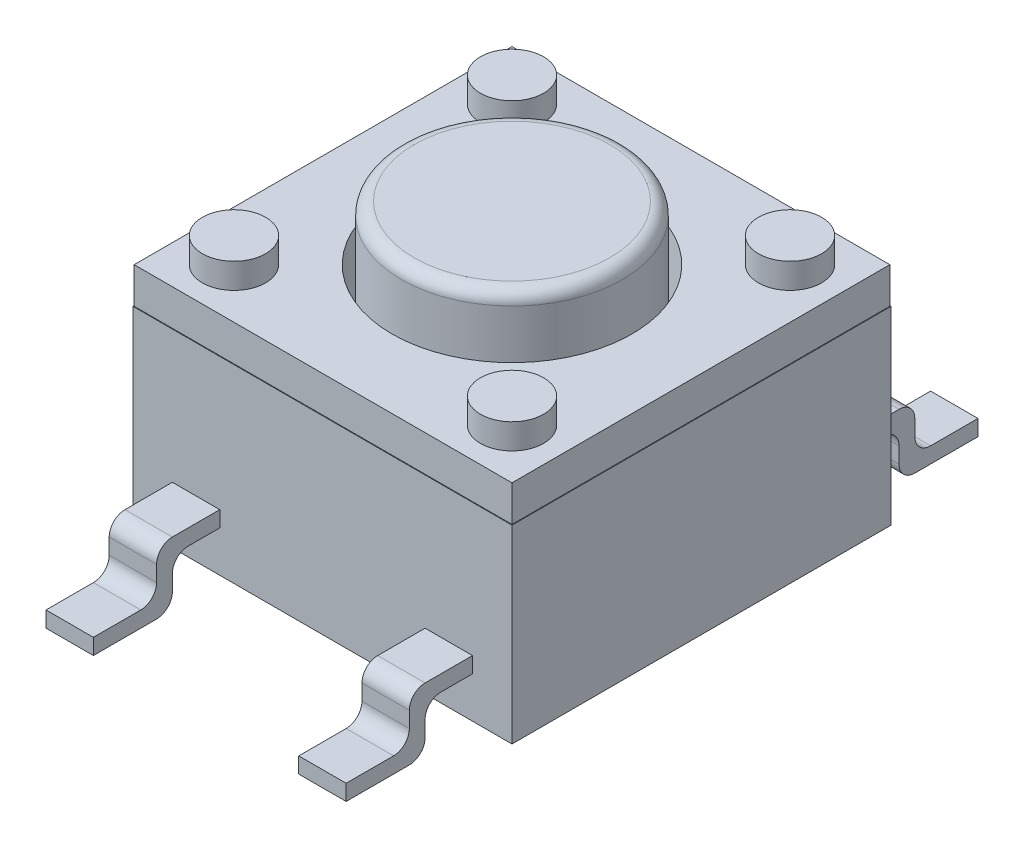
SolidWorks part; units mm, degrees
ref_plane "Front Plane" through (0, 0, 0) normal (0, 0, 1) x (1, 0, 0)
ref_plane "Top Plane" through (0, 0, 0) normal (0, 1, 0) x (1, 0, 0)
ref_plane "Right Plane" through (0, 0, 0) normal (1, 0, 0) x (0, 0, -1)
sketch "Sketch1" plane through (0, 0, 0) normal (0, 1, 0) x (1, 0, 0)
  line L1 (-3, 3) -> (3, 3)
  line L2 (-3, 3) -> (-3, -3)
  line L3 (-3, -3) -> (3, -3)
  line L4 (3, 3) -> (3, -3)
  circle A0 centre (0, 0) radius 1.9
  point P4 (-3, 0)
  point P6 (0, 3)
  dimension "D2" = 3.8
  dimension "D1" = 6
extrude "Extrude1" add sketch "Sketch1" along normal blind 3
sketch "Sketch2" plane through (0, 3, 0) normal (0, 1, 0) x (1, 0, 0)
  line L8 (-2.99, 2.99) -> (-2.99, -2.99)
  line L9 (-2.99, -2.99) -> (2.99, -2.99)
  line L10 (2.99, -2.99) -> (2.99, 2.99)
  line L11 (2.99, 2.99) -> (-2.99, 2.99)
  line L12 (-2.99, 2.99) -> (-2.99, -2.99)
  line L13 (-2.99, -2.99) -> (2.99, -2.99)
  line L14 (2.99, -2.99) -> (2.99, 2.99)
  line L15 (2.99, 2.99) -> (-2.99, 2.99)
  circle A0 centre (0, 0) radius 1.9 construction
  circle A1 centre (0, 0) radius 1.9
  dimension "D1" = 0.01
extrude "Extrude2" add sketch "Sketch2" along normal blind 0.57
sketch "Sketch3" plane through (0, 3.57, 0) normal (0, 1, 0) x (1, 0, 0)
  line L0 (-3, 3) -> (-3, -3) construction
  line L1 (3, 3) -> (-3, 3) construction
  line L2 (3, -3) -> (3, 3) construction
  line L3 (-3, -3) -> (3, -3) construction
  circle A0 centre (-2.2, 2.2) radius 0.5
  circle A1 centre (2.2, 2.2) radius 0.5
  circle A2 centre (2.2, -2.2) radius 0.5
  circle A3 centre (-2.2, -2.2) radius 0.5
  dimension "D1" = 1
  dimension "D2" = 0.8
  dimension "D3" = 0.8
  dimension "D4" = 0.8
  dimension "D5" = 0.8
extrude "Extrude3" add sketch "Sketch3" along normal blind 0.4
sketch "Sketch4" plane through (0, 3.57, 0) normal (0, 1, 0) x (1, 0, 0)
  circle A0 centre (0, 0) radius 1.75
  dimension "D1" = 3.5
extrude "Extrude4" add sketch "Sketch4" along normal blind 0.87 and the other way blind 3
fillet "Fillet1" radius 0.2 1 edges at (0, 4.44, 1.75)
ref_plane "Plane1" through (2, 0, 0) normal (1, 0, 0) x (0, 0, -1)
sketch "Sketch5" plane through (2, 0, 0) normal (1, 0, 0) x (0, 0, -1)
  line L0 (3.75, 0.9) -> (3.75, 0.15) construction
  line L1 (-5, 0.15) -> (-4, 0.15)
  line L2 (-5, -0.1) -> (-3.75, -0.1)
  line L3 (0, 5.8909) -> (0, -2.7526) construction
  line L4 (-5, 0.15) -> (-5, -0.1)
  line L5 (5, 0.15) -> (5, -0.1)
  line L6 (-4, 0.9) -> (-3, 0.9)
  line L7 (-3, 0) -> (3, 0) construction
  line L8 (-3, 0.9) -> (3, 0.9) construction
  line L9 (-3, -0.1) -> (3, -0.1) construction
  line L10 (4, 0.9) -> (4, 0.15) construction
  line L11 (-4, 0.9) -> (-4, 0.15) construction
  line L12 (-4, 3) -> (-4, 0)
  line L13 (-4, 0.9) -> (-4, 0.15)
  line L14 (5, 5.8909) -> (5, -2.7526) construction
  line L15 (4, 3) -> (4, 0)
  line L16 (4, 0.9) -> (4, 0.15)
  line L17 (-5, 5.8909) -> (-5, -2.7526) construction
  line L18 (-3.75, 0.65) -> (-3, 0.65)
  line L19 (-3.75, 0.65) -> (-3.75, -0.1)
  line L20 (-3.75, 0.9) -> (-3.75, 0.15) construction
  line L21 (3.75, 0.65) -> (3.75, -0.1)
  line L22 (-4, 0.65) -> (4, 0.65) construction
  line L23 (4, 0.15) -> (5, 0.15)
  line L24 (-5, 0.15) -> (5, 0.15) construction
  line L25 (3.75, -0.1) -> (5, -0.1)
  line L26 (-5, -0.1) -> (5, -0.1) construction
  line L27 (-4, 0.9) -> (4, 0.9) construction
  line L28 (-3, 3) -> (-3, 0) construction
  line L29 (-3, 0.9) -> (-3, 0.65)
  line L30 (3, 3) -> (3, 0) construction
  line L31 (3, 0.9) -> (3, 0.65)
  line L32 (3, 0.65) -> (3.75, 0.65)
  line L33 (3, 0.9) -> (4, 0.9)
  dimension "D2" = 0.1
  dimension "D3" = 10
  dimension "D10" = 5
  dimension "D7" = 0.25
  dimension "D9" = 0.25
  dimension "D1" = 0.25
  dimension "D4" = 1
  dimension "D5" = 1
  dimension "D6" = 1
  dimension "D8" = 0.25
extrude "Extrude5" add sketch "Sketch5" along normal mid plane 0.75
fillet "Fillet2" radius 0.25 8 edges at (2, -0.1, -3.75) (2, 0.65, -3.75) (2, 0.15, -4) (2, 0.9, -4) (2, -0.1, 3.75) (2, 0.65, 3.75) (2, 0.15, 4) (2, 0.9, 4)
mirror "Mirror1" about plane through (0, 0, 0) normal (1, 0, 0) of "Fillet2", "Extrude5"
